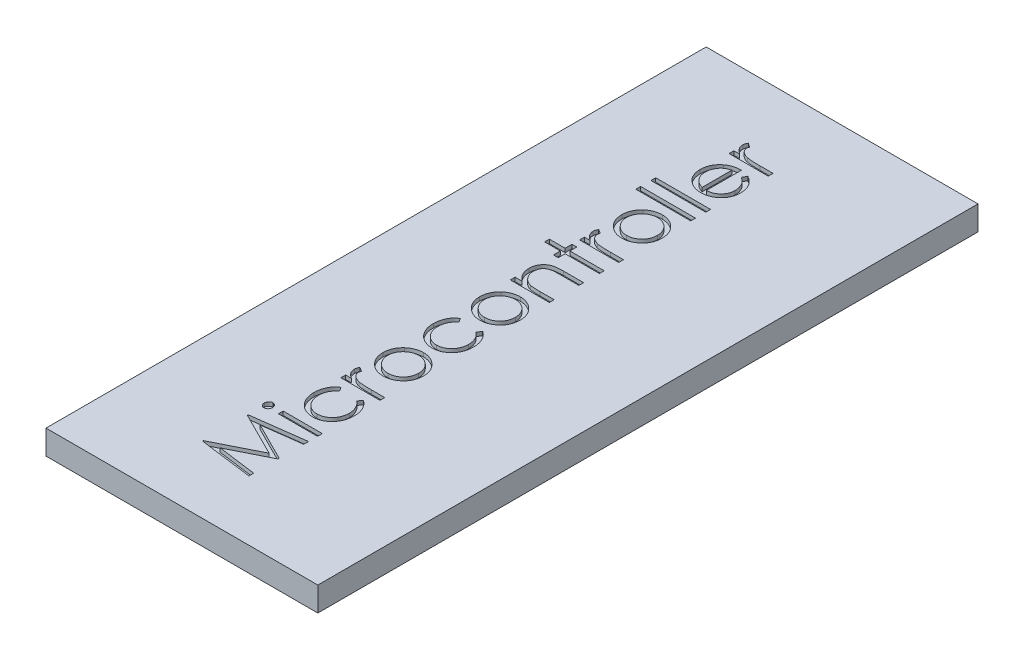
SolidWorks part; units mm, degrees
material "Silicon"
ref_plane "Front Plane" through (0, 0, 0) normal (0, 0, 1) x (1, 0, 0)
ref_plane "Top Plane" through (0, 0, 0) normal (0, 1, 0) x (1, 0, 0)
ref_plane "Right Plane" through (0, 0, 0) normal (1, 0, 0) x (0, 0, -1)
sketch "Sketch1" plane through (0, 0, 0) normal (0, 1, 0) x (1, 0, 0)
  line L1 (-8.89, -21.59) -> (8.89, -21.59)
  line L2 (-8.89, -21.59) -> (-8.89, 21.59)
  line L3 (-8.89, 21.59) -> (8.89, 21.59)
  line L4 (8.89, -21.59) -> (8.89, 21.59)
  line L5 (-8.89, -21.59) -> (8.89, 21.59) construction
  line L6 (-8.89, 21.59) -> (8.89, -21.59) construction
  point P0 (0, 0)
  dimension "D1" = 17.78
  dimension "D2" = 43.18
extrude "Boss-Extrude1" add sketch "Sketch1" along normal blind 1.5875
sketch "Sketch2" plane through (0, 1.5875, 0) normal (0, 1, 0) x (1, 0, 0)
  line L0 (0.4569, -17.9364) -> (0.4569, 16.32) construction
  text T0 "Microcontroller"
  point P2 (0, -17.9364)
  point P3 (0.4569, 16.32)
  point P5 (3.7504, 14.1331)
  point P6 (3.6983, -21.59)
extrude "Cut-Extrude1" cut sketch "Sketch2" against normal blind 0.254
